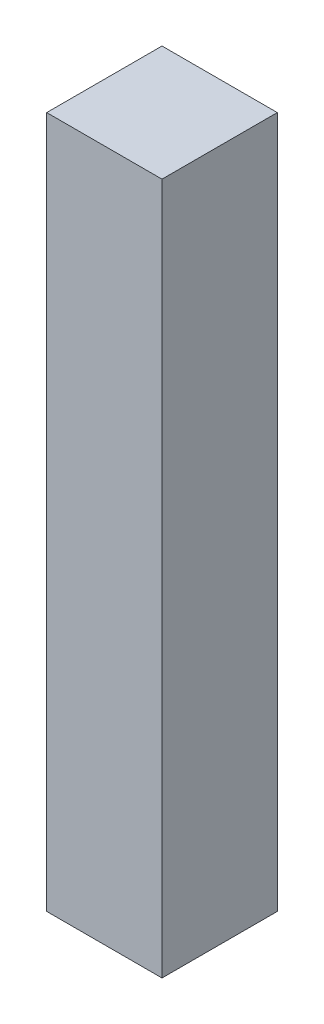
SolidWorks part; units mm, degrees
ref_plane "Front Plane" through (0, 0, 0) normal (0, 0, 1) x (1, 0, 0)
ref_plane "Top Plane" through (0, 0, 0) normal (0, 1, 0) x (1, 0, 0)
ref_plane "Right Plane" through (0, 0, 0) normal (1, 0, 0) x (0, 0, -1)
sketch "Sketch1" plane through (0, 0, 0) normal (0, 1, 0) x (1, 0, 0)
  line L1 (0, 0) -> (101.6, 0)
  line L2 (0, 0) -> (0, -101.6)
  line L3 (0, -101.6) -> (101.6, -101.6)
  line L4 (101.6, 0) -> (101.6, -101.6)
  dimension "D1" = 101.6
  dimension "D2" = 101.6
extrude "Boss-Extrude1" add sketch "Sketch1" along normal blind 609.6
